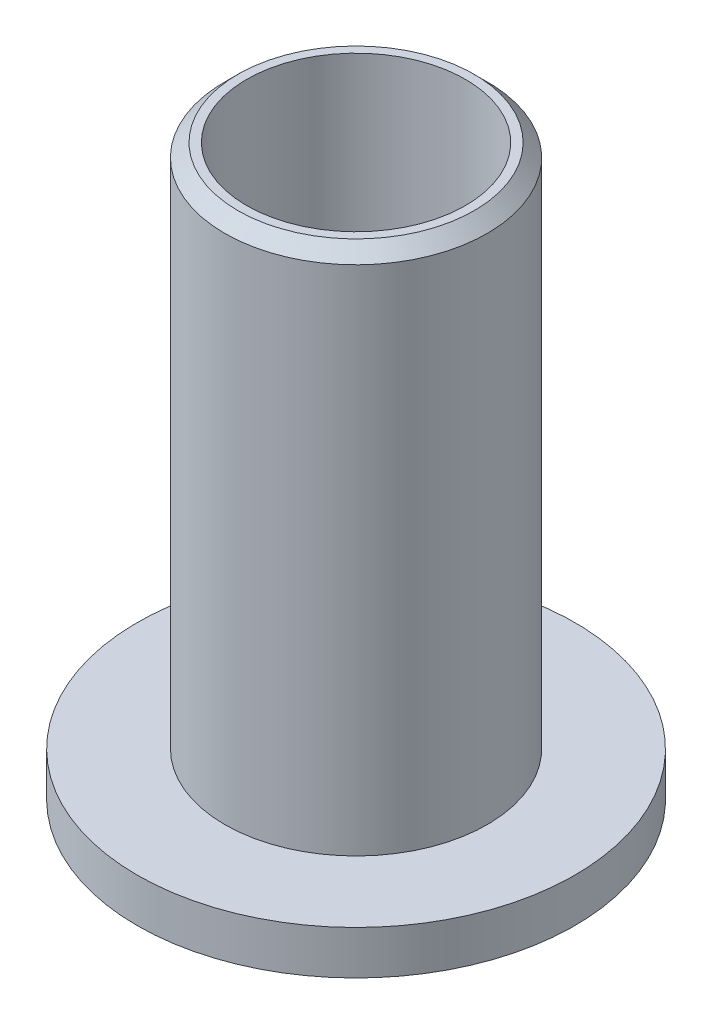
SolidWorks part; units mm, degrees
ref_plane "Front Plane" through (0, 0, 0) normal (0, 0, 1) x (1, 0, 0)
ref_plane "Top Plane" through (0, 0, 0) normal (0, 1, 0) x (1, 0, 0)
ref_plane "Right Plane" through (0, 0, 0) normal (1, 0, 0) x (0, 0, -1)
sketch "Sketch1" plane through (0, 0, 0) normal (0, 1, 0) x (1, 0, 0)
  circle A1 centre (0, 0) radius 5
  dimension "D1" = 10
extrude "Boss-Extrude1" add sketch "Sketch1" along normal blind 1
sketch "Sketch2" plane through (0, 1, 0) normal (0, 1, 0) x (1, 0, 0)
  circle A0 centre (0, 0) radius 3
extrude "Boss-Extrude2" add sketch "Sketch2" along normal blind 12
chamfer "Chamfer1" distance 0.3 angle 45 1 edges at (0, 13, 3)
sketch "Sketch3" plane through (0, 13, 0) normal (0, 1, 0) x (1, 0, 0)
  circle A0 centre (0, 0) radius 2.5
extrude "Cut-Extrude1" cut sketch "Sketch3" against normal through all both and the other way through all
